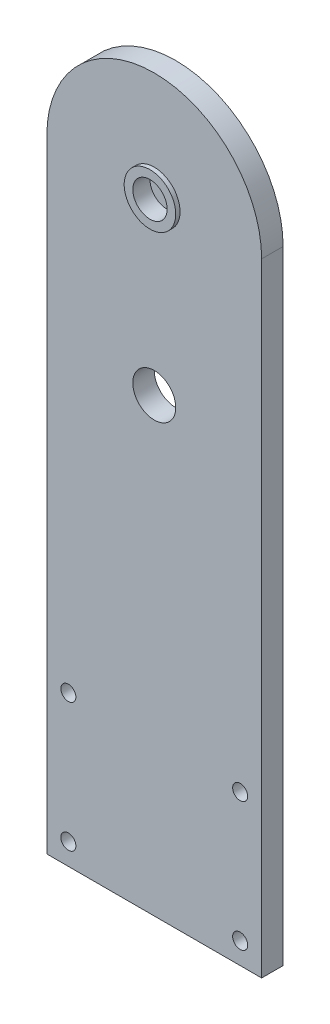
SolidWorks part; units mm, degrees
ref_plane "Front Plane" through (0, 0, 0) normal (0, 0, 1) x (1, 0, 0)
ref_plane "Top Plane" through (0, 0, 0) normal (0, 1, 0) x (1, 0, 0)
ref_plane "Right Plane" through (0, 0, 0) normal (1, 0, 0) x (0, 0, -1)
sketch "Sketch1" plane through (0, 0, 0) normal (0, 0, 1) x (1, 0, 0)
  line L1 (-25, -145) -> (25, -145)
  line L2 (-25, -145) -> (-25, 0)
  line L4 (25, -145) -> (25, 0)
  arc A0 (25, 0) -> (-25, 0) centre (0, 0) ccw
  dimension "D1" = 50
  dimension "D2" = 145
  dimension "D3" = 25
extrude "Boss-Extrude1" add sketch "Sketch1" along normal blind 5
sketch "Sketch2" plane through (0, 0, 5) normal (0, 0, 1) x (1, 0, 0)
  circle A0 centre (0, 0) radius 4
  dimension "D1" = 8
extrude "Cut-Extrude1" cut sketch "Sketch2" against normal blind 3
sketch "Sketch3" plane through (0, 0, 5) normal (0, 0, 1) x (1, 0, 0)
  circle A0 centre (0, 0) radius 4
  circle A1 centre (0, 0) radius 6
  dimension "D1" = 12
extrude "Boss-Extrude2" add sketch "Sketch3" along normal blind 1
sketch "Sketch4" plane through (0, 0, 5) normal (0, 0, 1) x (1, 0, 0)
  line L0 (-25, -145) -> (25, -145) construction
  line L1 (-25, 0) -> (-25, -145) construction
  line L2 (0, -117.7542) -> (0, -106.692) construction
  circle A0 centre (-20, -140) radius 1.75
  circle A1 centre (-20, -110) radius 1.75
  circle A2 centre (20, -110) radius 1.75
  circle A3 centre (20, -140) radius 1.75
  dimension "D1" = 3.5
  dimension "D4" = 3.5
  dimension "D2" = 5
  dimension "D3" = 5
  dimension "D5" = 35
extrude "Cut-Extrude2" cut sketch "Sketch4" against normal through all
sketch "Sketch5" plane through (0, 0, 5) normal (0, 0, 1) x (1, 0, 0)
  circle A0 centre (0, -40) radius 5
  dimension "D1" = 10
  dimension "D2" = 40
extrude "Cut-Extrude3" cut sketch "Sketch5" against normal through all
